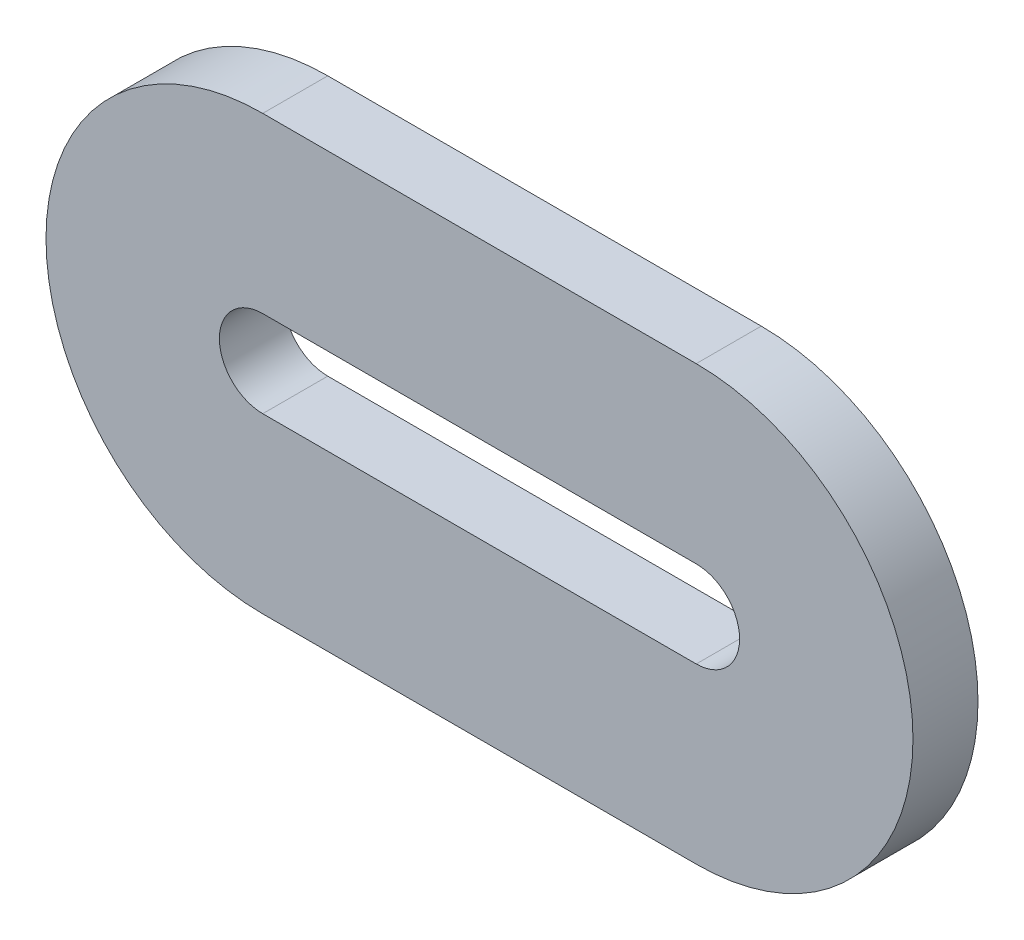
SolidWorks part; units mm, degrees
ref_plane "Front Plane" through (0, 0, 0) normal (0, 0, 1) x (1, 0, 0)
ref_plane "Top Plane" through (0, 0, 0) normal (0, 1, 0) x (1, 0, 0)
ref_plane "Right Plane" through (0, 0, 0) normal (1, 0, 0) x (0, 0, -1)
sketch "Sketch1" plane through (0, 0, 0) normal (0, 0, 1) x (1, 0, 0)
  line L0 (0, 0) -> (20, 0) construction
  line L1 (0, 2) -> (20, 2)
  line L2 (0, -2) -> (20, -2)
  line L3 (0, 0) -> (20, 0) construction
  line L4 (0, 10) -> (20, 10)
  line L5 (0, -10) -> (20, -10)
  arc A0 (0, 2) -> (0, -2) centre (0, 0) ccw
  arc A1 (20, -2) -> (20, 2) centre (20, 0) ccw
  arc A2 (0, 10) -> (0, -10) centre (0, 0) ccw
  arc A3 (20, -10) -> (20, 10) centre (20, 0) ccw
  point P3 (10, 0)
  point P10 (10, 0)
  dimension "D1" = 4
  dimension "D2" = 20
  dimension "D3" = 8
extrude "Boss-Extrude1" add sketch "Sketch1" along normal blind 3
